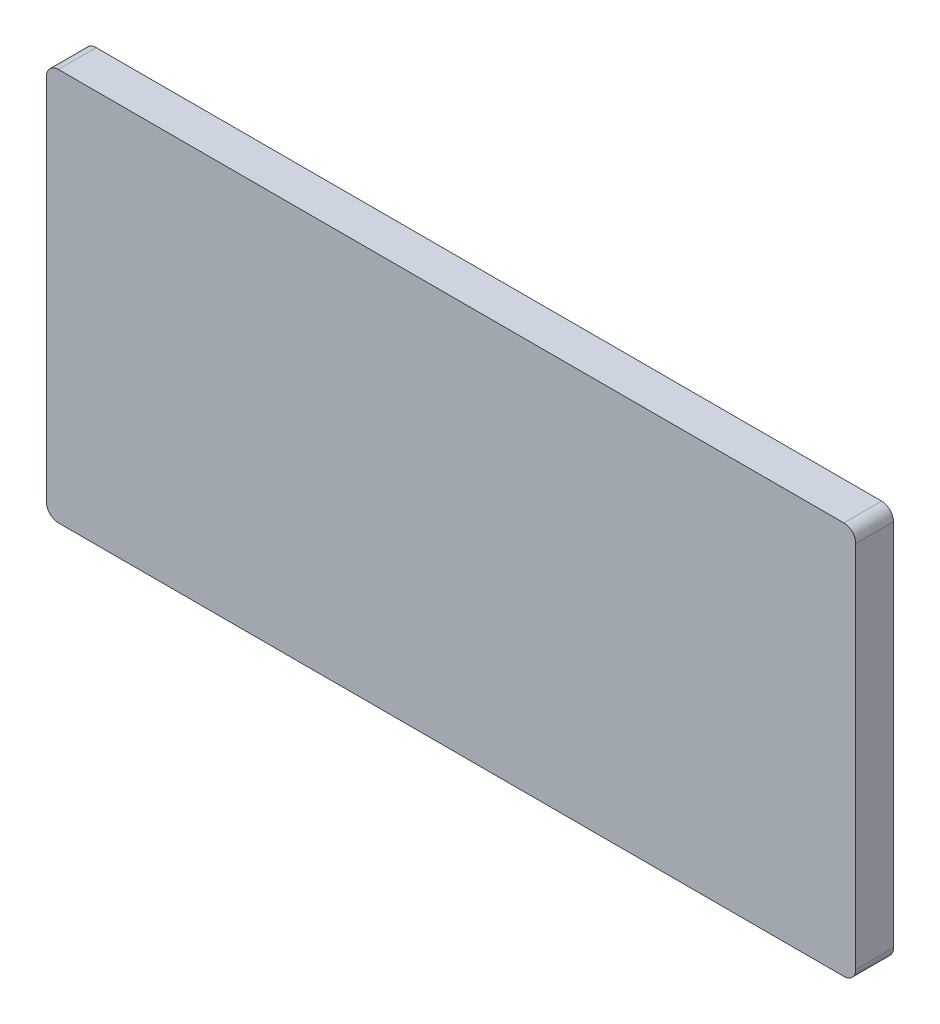
SolidWorks part; units mm, degrees
material "Acrylic (Medium-high impact)"
ref_plane "Front Plane" through (0, 0, 0) normal (0, 0, 1) x (1, 0, 0)
ref_plane "Top Plane" through (0, 0, 0) normal (0, 1, 0) x (1, 0, 0)
ref_plane "Right Plane" through (0, 0, 0) normal (1, 0, 0) x (0, 0, -1)
sketch "Sketch1" plane through (0, 0, 0) normal (0, 0, 1) x (1, 0, 0)
  line L1 (34, 16.5) -> (-34, 16.5)
  line L2 (34, 16.5) -> (34, -16.5)
  line L3 (34, -16.5) -> (-34, -16.5)
  line L4 (-34, 16.5) -> (-34, -16.5)
  line L5 (34, 16.5) -> (-34, -16.5) construction
  line L6 (34, -16.5) -> (-34, 16.5) construction
  point P18 (0, 0)
  dimension "D1" = 68
  dimension "D2" = 33
extrude "Boss-Extrude1" add sketch "Sketch1" along normal blind 3.175
fillet "Fillet1" radius 1 4 edges at (34, -16.5, 1.5875) (-34, -16.5, 1.5875) (-34, 16.5, 1.5875) (34, 16.5, 1.5875)
sketch "Sketch2" plane through (0, 0, 0) normal (0, 0, -1) x (-1, 0, 0)
  line L0 (0, 0) -> (20.5, 0) construction
  line L1 (1.7463, 0) -> (-1.7463, 0) construction
  line L2 (0, 1.7463) -> (0, -1.7463) construction
  line L3 (-31.75, 14.25) -> (-29.25, 14.25) construction
  line L4 (-31.75, 15.95) -> (-29.25, 15.95)
  line L5 (-31.75, 12.55) -> (-29.25, 12.55)
  line L6 (-31.75, -14.25) -> (-29.25, -14.25) construction
  line L7 (-31.75, -15.95) -> (-29.25, -15.95)
  line L8 (-31.75, -12.55) -> (-29.25, -12.55)
  line L9 (-20.5, 0) -> (-17.5, 0) construction
  line L10 (-20.5, 2.15) -> (-17.5, 2.15)
  line L11 (-20.5, -2.15) -> (-17.5, -2.15)
  circle A0 centre (20.5, 0) radius 2.15
  circle A1 centre (31.75, -14.25) radius 1.7
  circle A2 centre (31.75, 14.25) radius 1.7
  circle A3 centre (-31.75, 14.25) radius 1.7 construction
  circle A4 centre (-20.5, 0) radius 2.15 construction
  circle A5 centre (-31.75, -14.25) radius 1.7 construction
  arc A6 (-31.75, 15.95) -> (-31.75, 12.55) centre (-31.75, 14.25) ccw
  arc A7 (-29.25, 12.55) -> (-29.25, 15.95) centre (-29.25, 14.25) ccw
  arc A8 (-31.75, -15.95) -> (-31.75, -12.55) centre (-31.75, -14.25) cw
  arc A9 (-29.25, -12.55) -> (-29.25, -15.95) centre (-29.25, -14.25) cw
  arc A10 (-20.5, 2.15) -> (-20.5, -2.15) centre (-20.5, 0) ccw
  arc A11 (-17.5, -2.15) -> (-17.5, 2.15) centre (-17.5, 0) ccw
  point P19 (-30.5, 14.25)
  point P25 (-30.5, -14.25)
  point P30 (-19, 0)
  dimension "D2" = 4.3
  dimension "D3" = 3.4
  dimension "D5" = 31.75
  dimension "D7" = 3
  dimension "D1" = 20.5
  dimension "D4" = 14.25
  dimension "D6" = 2.5
extrude "Cut-Extrude2" cut sketch "Sketch2" against normal blind 1.25
